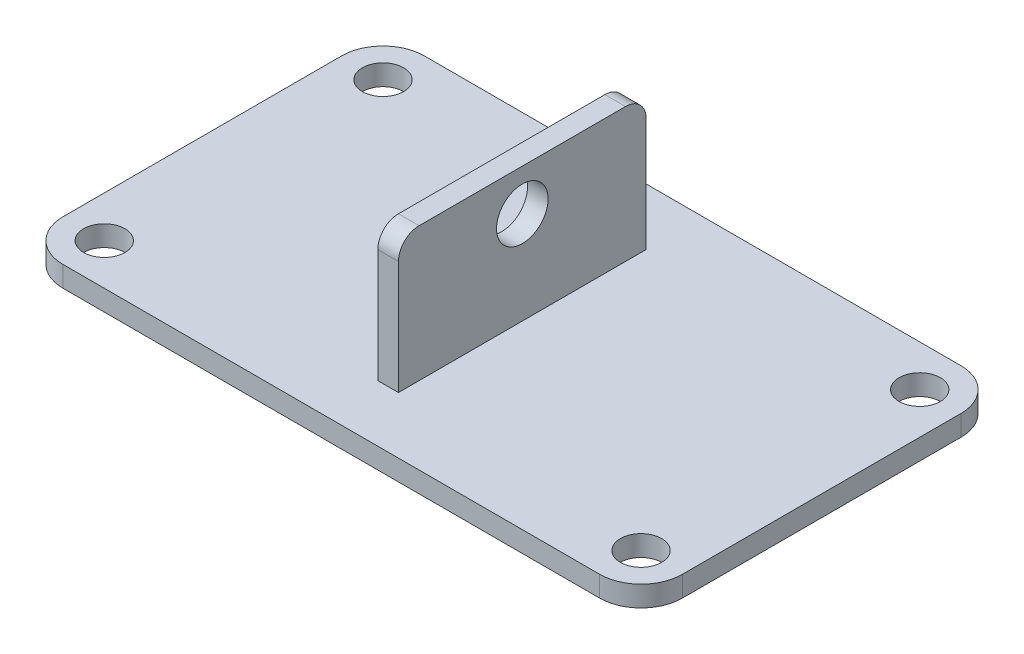
SolidWorks part; units mm, degrees
ref_plane "Front Plane" through (0, 0, 0) normal (0, 0, 1) x (1, 0, 0)
ref_plane "Top Plane" through (0, 0, 0) normal (0, 1, 0) x (1, 0, 0)
ref_plane "Right Plane" through (0, 0, 0) normal (1, 0, 0) x (0, 0, -1)
sketch "Sketch4" plane through (0, 0, 0) normal (0, 1, 0) x (1, 0, 0)
  line L0 (-130, -87.5) -> (130, -87.5)
  line L1 (-150, -67.5) -> (-150, 67.5)
  line L2 (-130, 87.5) -> (130, 87.5)
  line L3 (150, -67.5) -> (150, 67.5)
  line L4 (-150, -87.5) -> (150, 87.5) construction
  line L5 (-150, 87.5) -> (150, -87.5) construction
  arc A0 (150, 67.5) -> (130, 87.5) centre (130, 67.5) ccw
  arc A1 (150, -67.5) -> (130, -87.5) centre (130, -67.5) cw
  arc A2 (-130, -87.5) -> (-150, -67.5) centre (-130, -67.5) cw
  arc A3 (-150, 67.5) -> (-130, 87.5) centre (-130, 67.5) cw
  circle A4 centre (-130, 67.5) radius 10
  circle A5 centre (-130, -67.5) radius 10
  circle A6 centre (130, 67.5) radius 10
  circle A7 centre (130, -67.5) radius 10
  point P0 (0, 0)
  point P21 (0, 0)
  point P22 (0, 0)
  dimension "D3" = 20
  dimension "D4" = 20
  dimension "D5" = 20
  dimension "D6" = 20
  dimension "D7" = 20
  dimension "D1" = 175
  dimension "D2" = 300
extrude "Boss-Extrude2" add sketch "Sketch4" along normal blind 10
sketch "Sketch5" plane through (0, 0, 0) normal (1, 0, 0) x (0, 0, -1)
  line L0 (-60, 10) -> (-60, 65)
  line L1 (-60, 10) -> (60, 10)
  line L2 (0, 10) -> (0, 42.5) construction
  line L3 (-50, 75) -> (50, 75)
  line L4 (60, 10) -> (60, 65)
  line L5 (-67.5, 10) -> (67.5, 10) construction
  circle A0 centre (0, 55) radius 12.5
  arc A1 (60, 65) -> (50, 75) centre (50, 65) ccw
  arc A2 (-60, 65) -> (-50, 75) centre (-50, 65) cw
  point P2 (0, 0)
  point P9 (60, 75)
  point P14 (-60, 75)
  point P16 (0, 0)
  point P17 (0, 0)
  point P19 (0, 10)
  dimension "D4" = 25
  dimension "D5" = 10
  dimension "D1" = 60
  dimension "D2" = 65
  dimension "D3" = 45
extrude "Boss-Extrude3" add sketch "Sketch5" along normal mid plane 10 separate body
